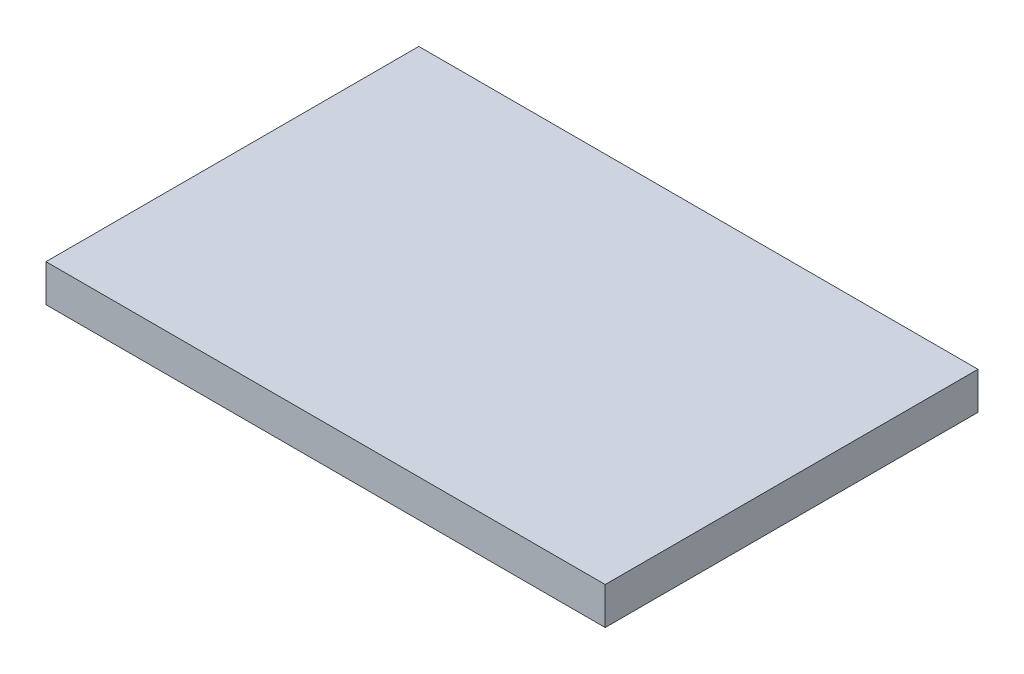
SolidWorks part; units mm, degrees
ref_plane "Front Plane" through (0, 0, 0) normal (0, 0, 1) x (1, 0, 0)
ref_plane "Top Plane" through (0, 0, 0) normal (0, 1, 0) x (1, 0, 0)
ref_plane "Right Plane" through (0, 0, 0) normal (1, 0, 0) x (0, 0, -1)
sketch "Sketch1" plane through (0, 0, 0) normal (0, 1, 0) x (1, 0, 0)
  line L1 (0, 0) -> (75, 0)
  line L2 (0, 0) -> (0, 50)
  line L3 (0, 50) -> (75, 50)
  line L4 (75, 0) -> (75, 50)
  dimension "D1" = 75
  dimension "0.05" = 50
extrude "Boss-Extrude1" add sketch "Sketch1" along normal blind 5 contours L3 L4 L1 L2
